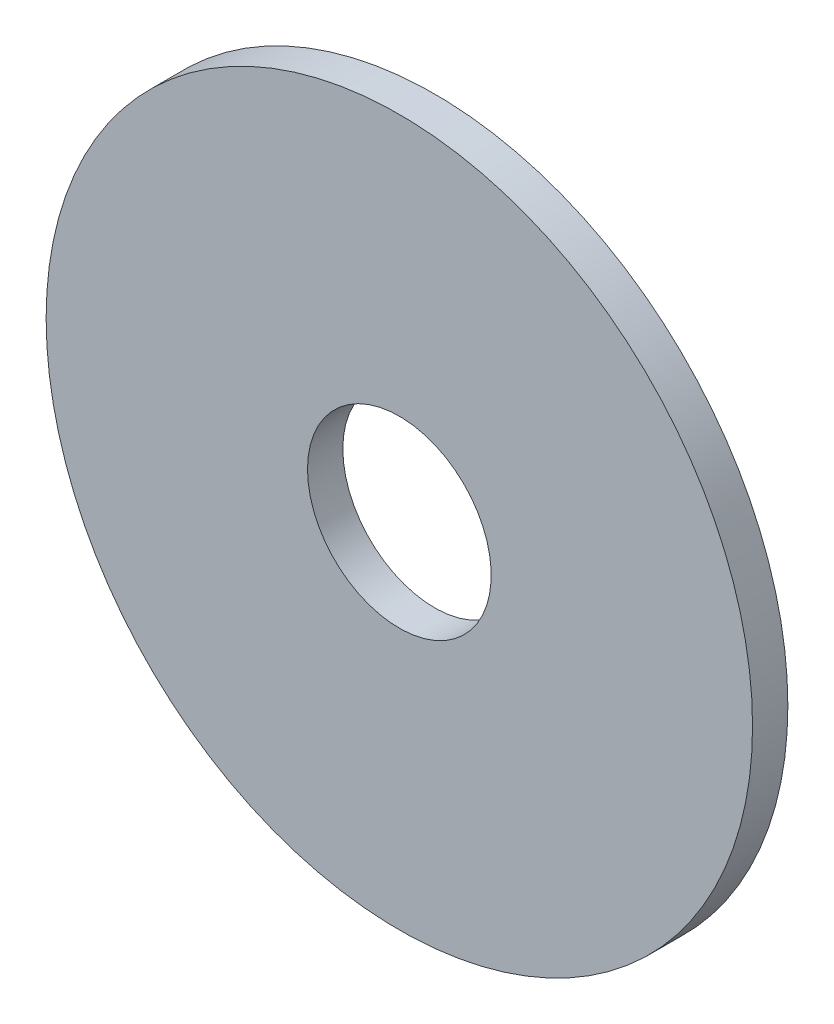
SolidWorks part; units mm, degrees
ref_plane "Front Plane" through (0, 0, 0) normal (0, 0, 1) x (1, 0, 0)
ref_plane "Top Plane" through (0, 0, 0) normal (0, 1, 0) x (1, 0, 0)
ref_plane "Right Plane" through (0, 0, 0) normal (1, 0, 0) x (0, 0, -1)
ref_plane "Plane1" through (0, 0, 0) normal (0, -1, 0) x (1, 0, 0)
sketch "Sketch1" plane through (0, 0, 0) normal (0, -1, 0) x (1, 0, 0)
  line L0 (10, 0) -> (10, 1)
  line L1 (10, 1) -> (2.6, 1)
  line L2 (2.6, 1) -> (2.6, 0)
  line L3 (2.6, 0) -> (10, 0)
  line L4 (0, 1) -> (0, 0) construction
revolve "Revolve1" add sketch "Sketch1" angle 360 about L4
